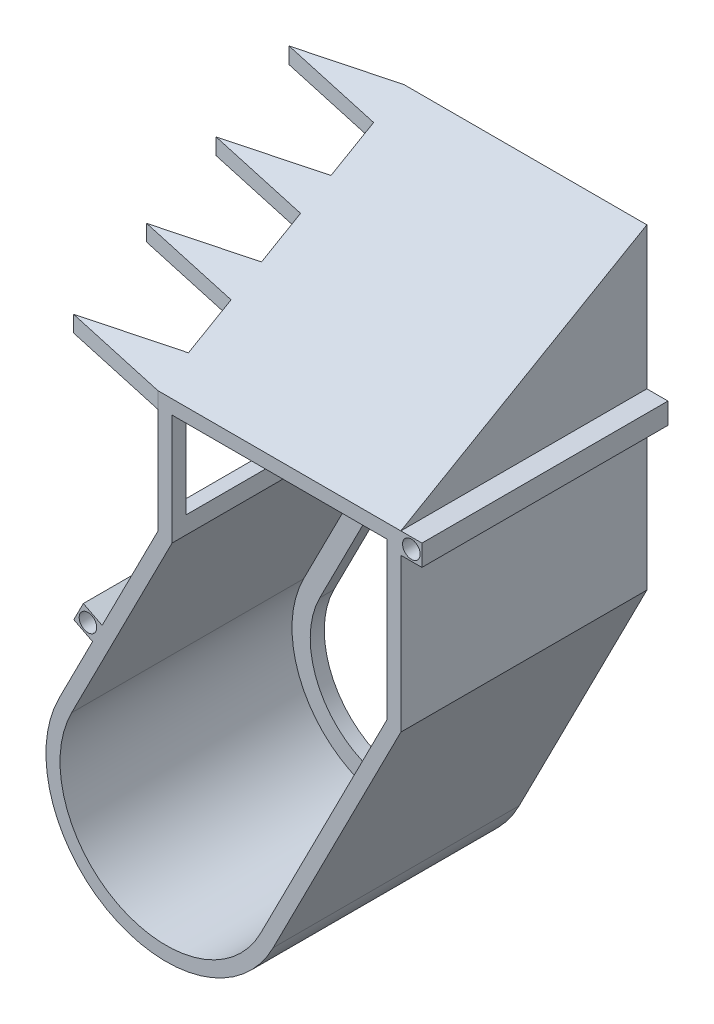
SolidWorks part; units mm, degrees
ref_plane "Front Plane" through (0, 0, 0) normal (0, 0, 1) x (1, 0, 0)
ref_plane "Top Plane" through (0, 0, 0) normal (0, 1, 0) x (1, 0, 0)
ref_plane "Right Plane" through (0, 0, 0) normal (1, 0, 0) x (0, 0, -1)
sketch "Sketch1" plane through (0, 0, 0) normal (0, 0, 1) x (1, 0, 0)
  line L0 (0, 0) -> (0, 41.4835) construction
  line L1 (-38.8753, 168.2436) -> (48.8659, 168.2436)
  line L2 (48.8659, 168.2436) -> (48.8659, 53.9436)
  line L3 (48.8659, 53.9436) -> (2.7405, -36.5827)
  line L4 (-38.8753, 168.2436) -> (-38.8753, 72.9936)
  line L5 (-38.8753, 72.9936) -> (-74.6225, 2.8357)
  line L6 (-7.6515, -31.2877) -> (15.4112, 13.9754)
  line L7 (15.4112, 13.9754) -> (-46.9334, 31.488)
  line L8 (-46.9334, 31.488) -> (-64.2305, -2.4593)
  circle A0 centre (-23.0776, 59.2635) radius 3.175
  circle A1 centre (22.1344, 59.2635) radius 3.175
  arc A2 (-64.2305, -2.4593) -> (-7.6515, -31.2877) centre (-35.941, -16.8735) ccw
  arc A3 (-74.6225, 2.8357) -> (2.7405, -36.5827) centre (-35.941, -16.8735) ccw
  point P8 (0, 0)
  point P20 (0, 0)
  point P21 (9.6455, 2.8357)
  point P22 (9.6455, 2.8357)
  point P23 (-46.9334, 31.488)
  point P24 (9.6455, 2.8357)
  point P25 (14.1522, 11.5046)
  dimension "D1" = 63.5
  dimension "D2" = 45.212
  dimension "D3" = 6.35
  dimension "D4" = 6.35
  dimension "D11" = 101.6
  dimension "D5" = 77.216
  dimension "D6" = 95.758
  dimension "D7" = 35.941
  dimension "D8" = 17.78
  dimension "D9" = 153
  dimension "D10" = 114.3
  dimension "D12" = 78.74
  dimension "D13" = 95.25
  dimension "D14" = 19.05
  dimension "D15" = 38.1
  dimension "D16" = 50.8
extrude "Boss-Extrude1" add sketch "Sketch1" along normal blind 88.9
sketch "Sketch2" plane through (-38.8753, 0, 0) normal (-1, 0, 0) x (0, 0, 1)
  line L0 (0, 168.2436) -> (88.9, 116.9171)
  line L1 (88.9, 168.2436) -> (88.9, 72.9936) construction
  line L2 (88.9, 116.9171) -> (88.9, 168.2436)
  line L3 (88.9, 168.2436) -> (0, 168.2436)
  dimension "D1" = 30
extrude "Cut-Extrude1" cut sketch "Sketch2" against normal through all
sketch "Sketch3" plane through (0, 0, 88.9) normal (0, 0, 1) x (1, 0, 0)
  line L10 (43.7859, 111.8371) -> (-33.7953, 111.8371)
  line L11 (-33.7953, 111.8371) -> (-33.7953, 71.774)
  line L12 (-33.7953, 71.774) -> (-70.0962, 0.5294)
  line L13 (-1.7858, -34.2764) -> (43.7859, 55.1632)
  line L14 (43.7859, 55.1632) -> (43.7859, 111.8371)
  line L15 (43.7859, 111.8371) -> (-33.7953, 111.8371)
  line L16 (-33.7953, 111.8371) -> (-33.7953, 71.774)
  line L17 (-33.7953, 71.774) -> (-70.0962, 0.5294)
  line L18 (-1.7858, -34.2764) -> (43.7859, 55.1632)
  line L19 (43.7859, 55.1632) -> (43.7859, 111.8371)
  arc A2 (-70.0962, 0.5294) -> (-1.7858, -34.2764) centre (-35.941, -16.8735) ccw
  arc A3 (-70.0962, 0.5294) -> (-1.7858, -34.2764) centre (-35.941, -16.8735) ccw
  dimension "D1" = 5.08
extrude "Cut-Extrude2" cut sketch "Sketch3" against normal blind 83.82
sketch "Sketch4" plane through (-38.8753, 0, 0) normal (-1, 0, 0) x (0, 0, 1)
  line L8 (83.82, 78.0736) -> (83.82, 113.9842)
  line L9 (83.82, 113.9842) -> (5.08, 159.4447)
  line L10 (5.08, 159.4447) -> (5.08, 78.0736)
  line L11 (5.08, 78.0736) -> (83.82, 78.0736)
  line L12 (83.82, 78.0736) -> (83.82, 113.9842)
  line L13 (83.82, 113.9842) -> (5.08, 159.4447)
  line L14 (5.08, 159.4447) -> (5.08, 78.0736)
  line L15 (5.08, 78.0736) -> (83.82, 78.0736)
  dimension "D1" = 5.08
extrude "Cut-Extrude3" cut sketch "Sketch4" along direction (1, 0, 0) on the side against the normal up to surface (82.6612 mm away)
sketch "Sketch5" plane through (0, 126.1827, 72.8516) normal (0, 0.866, 0.5) x (1, 0, 0)
  line L0 (-38.8753, 84.1218) -> (-74.8879, 77.7718)
  line L1 (-74.8879, 77.7718) -> (-38.8753, 71.4218)
  line L2 (-38.8753, 71.4218) -> (-38.8753, 84.1218)
  line L3 (-38.8753, 84.1218) -> (-38.8753, -18.5311) construction
  line L4 (-38.8753, 53.6418) -> (-74.8879, 47.2918)
  line L5 (-74.8879, 47.2918) -> (-38.8753, 40.9418)
  line L6 (-38.8753, 40.9418) -> (-38.8753, 53.6418)
  line L7 (-38.8753, 24.6489) -> (-74.8879, 18.2989)
  line L8 (-74.8879, 18.2989) -> (-38.8753, 11.9489)
  line L9 (-38.8753, -40.4929) -> (-38.8753, 36.4968) construction
  line L10 (-38.8753, 11.9489) -> (-38.8753, 24.6489)
  line L11 (-38.8753, -5.8311) -> (-74.8879, -12.1811)
  line L12 (-74.8879, -12.1811) -> (-38.8753, -18.5311)
  line L13 (-38.8753, -18.5311) -> (-38.8753, -5.8311)
  dimension "D1" = 12.7
  dimension "D2" = 20
  dimension "D3" = 17.78
  dimension "D4" = 17.78
  dimension "D5" = 20
  dimension "D6" = 12.7
  dimension "D7" = 20
  dimension "D8" = 20
extrude "Boss-Extrude2" add sketch "Sketch5" along direction (0, 1, 0) on the side against the normal up to surface (5.08 mm away)
sketch "Sketch6" plane through (0, 0, 88.9) normal (0, 0, 1) x (1, 0, 0)
  line L0 (48.8659, 116.9171) -> (56.4859, 116.9171)
  line L1 (56.4859, 116.9171) -> (56.4859, 109.2971)
  line L2 (56.4859, 109.2971) -> (48.8659, 109.2971)
  line L3 (48.8659, 53.9436) -> (48.8659, 116.9171) construction
  line L4 (48.8659, 109.2971) -> (48.8659, 116.9171)
  line L5 (-62.5146, 26.5988) -> (-59.0552, 33.3883)
  line L6 (-38.8753, 72.9936) -> (-74.6225, 2.8357) construction
  line L7 (-59.0552, 33.3883) -> (-65.8446, 36.8477)
  line L8 (-65.8446, 36.8477) -> (-69.304, 30.0582)
  line L9 (-69.304, 30.0582) -> (-62.5146, 26.5988)
  circle A0 centre (52.6759, 113.1071) radius 3.175
  circle A1 centre (-64.1796, 31.7233) radius 3.175
  dimension "D3" = 6.35
  dimension "D4" = 6.35
  dimension "D1" = 7.62
  dimension "D2" = 44.45
  dimension "D5" = 3.81
  dimension "D6" = 3.81
  dimension "D7" = 3.81
  dimension "D8" = 3.81
extrude "Boss-Extrude3" add sketch "Sketch6" against normal up to surface (88.9 mm away) up to face at (25.3094, 59.2635, 0)
